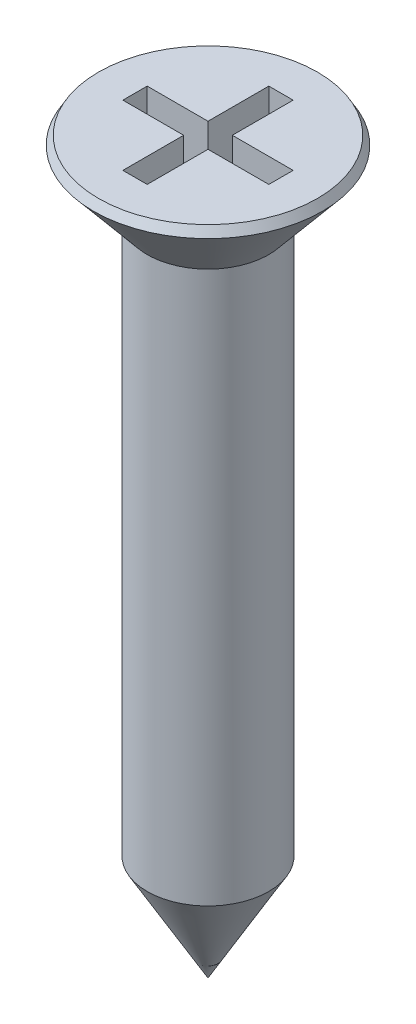
SolidWorks part; units mm, degrees
ref_plane "前视基准面" through (0, 0, 0) normal (0, 0, 1) x (1, 0, 0)
ref_plane "上视基准面" through (0, 0, 0) normal (0, 1, 0) x (1, 0, 0)
ref_plane "右视基准面" through (0, 0, 0) normal (1, 0, 0) x (0, 0, -1)
other "Configuration Table"
sketch "草图1" plane through (0, 0, 0) normal (0, 0, 1) x (1, 0, 0)
  line L0 (0, 0) -> (0, 34.6293) construction
  line L1 (0, 0) -> (0.5, 0.866)
  line L2 (0.5, 0.866) -> (0.5, 5.4)
  line L3 (0.5, 5.4) -> (1, 6)
  line L4 (1, 6) -> (0, 6)
  line L5 (0, 6) -> (0, 0)
  dimension "D1" = 30
  dimension "D2" = 0.5
  dimension "D3" = 6
  dimension "D4" = 1
  dimension "D5" = 0.6
revolve "旋转1" add sketch "草图1" angle 360 about L0
chamfer "倒角1" distance 0.1 angle 60 1 edges at (0, 6, -1)
sketch "草图2" plane through (0, 6, 0) normal (0, 1, 0) x (1, 0, 0)
  line L0 (-707.1068, -707.1068) -> (-0.1, -0.1) construction
  line L1 (-0.6, -0.1) -> (-0.1, -0.1)
  line L2 (-0.6, -0.1) -> (-0.6, 0.1)
  line L3 (-0.6, 0.1) -> (-0.1, 0.1)
  line L4 (0.6, -0.1) -> (0.6, 0.1)
  line L7 (0.1, -0.6) -> (0.1, -0.1)
  line L8 (-0.1, 0.6) -> (0.1, 0.6)
  line L9 (-0.1, -0.6) -> (-0.1, -0.1)
  line L10 (-0.1, -0.6) -> (0.1, -0.6)
  line L11 (0.1, -0.1) -> (0.6, -0.1)
  line L12 (0.1, 0.1) -> (0.1, 0.6)
  line L14 (0.1, 0.1) -> (707.5523, 707.5523) construction
  line L15 (-0.1, 0.1) -> (-0.1, 0.6)
  line L17 (0.1, 0.1) -> (0.6, 0.1)
  point P0 (0, 0)
  dimension "D1" = 1.2
  dimension "D2" = 0.2
extrude "切除-拉伸1" cut sketch "草图2" against normal blind 0.4
